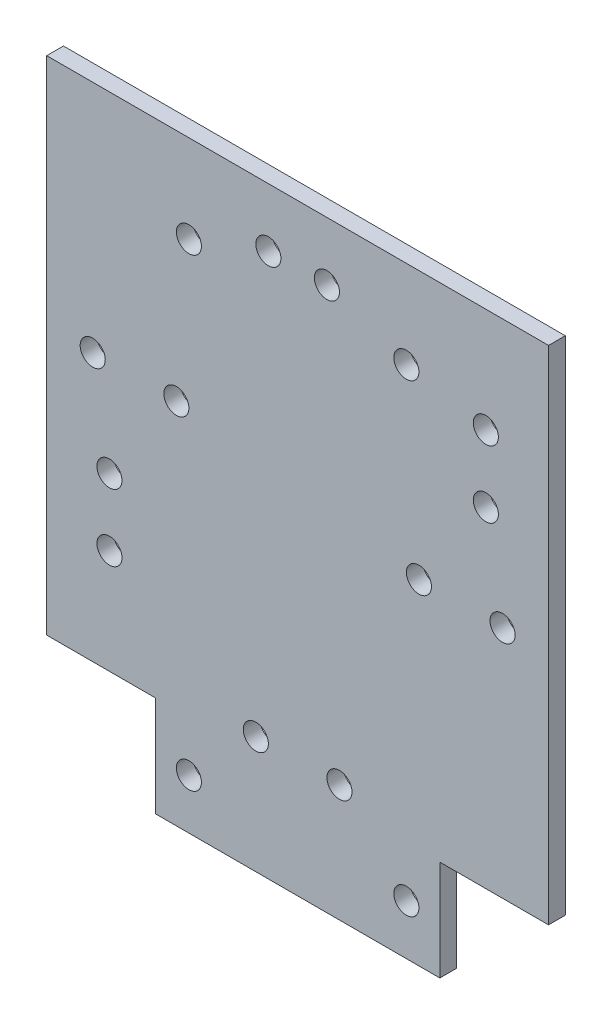
SolidWorks part; units mm, degrees
ref_plane "Plan de face" through (0, 0, 0) normal (0, 0, 1) x (1, 0, 0)
ref_plane "Plan de dessus" through (0, 0, 0) normal (0, 1, 0) x (1, 0, 0)
ref_plane "Plan de droite" through (0, 0, 0) normal (1, 0, 0) x (0, 0, -1)
sketch "Esquisse1" plane through (0, 0, 0) normal (0, 0, 1) x (1, 0, 0)
  line L0 (57.7642, 1.5445) -> (57.7642, -6.4555) construction
  line L1 (5.2642, 14.0445) -> (65.2642, 14.0445)
  line L2 (5.2642, 14.0445) -> (5.2642, -45.9555)
  line L3 (18.2642, -57.9555) -> (52.2642, -57.9555)
  line L4 (65.2642, 14.0445) -> (65.2642, -45.9555)
  line L5 (40.2642, -43.9555) -> (30.2642, -43.9555) construction
  line L6 (59.7642, -17.9555) -> (49.7642, -17.9555) construction
  line L7 (5.2642, -45.9555) -> (18.2642, -45.9555)
  line L8 (22.2642, 3.5445) -> (48.2642, 3.5445) construction
  line L9 (18.2642, -57.9555) -> (18.2642, -45.9555)
  line L10 (31.7642, 7.0445) -> (38.7642, 7.0445) construction
  line L11 (25.7642, 2.0445) -> (44.7642, 2.0445) construction
  line L12 (22.2642, -51.9555) -> (48.2642, -51.9555) construction
  line L13 (25.7642, 2.0445) -> (25.7642, -37.9555) construction
  line L14 (65.2642, -45.9555) -> (52.2642, -45.9555)
  line L15 (52.2642, -57.9555) -> (52.2642, -45.9555)
  line L16 (25.7642, -37.9555) -> (44.7642, -37.9555) construction
  line L17 (44.7642, 2.0445) -> (44.7642, -37.9555) construction
  line L18 (12.7642, -33.4555) -> (12.7642, -25.4555) construction
  line L19 (20.7642, -13.9555) -> (10.7642, -13.9555) construction
  circle A0 centre (57.7642, 1.5445) radius 1.5
  circle A1 centre (57.7642, -6.4555) radius 1.5
  circle A2 centre (12.7642, -33.4555) radius 1.5
  circle A3 centre (12.7642, -25.4555) radius 1.5
  circle A4 centre (40.2642, -43.9555) radius 1.5
  circle A5 centre (30.2642, -43.9555) radius 1.5
  circle A6 centre (49.7642, -17.9555) radius 1.5
  circle A7 centre (59.7642, -17.9555) radius 1.5
  circle A8 centre (31.7642, 7.0445) radius 1.5
  circle A9 centre (38.7642, 7.0445) radius 1.5
  circle A10 centre (22.2642, 3.5445) radius 1.5
  circle A11 centre (48.2642, 3.5445) radius 1.5
  circle A12 centre (20.7642, -13.9555) radius 1.5
  circle A13 centre (10.7642, -13.9555) radius 1.5
  circle A16 centre (22.2642, -51.9555) radius 1.5
  circle A17 centre (48.2642, -51.9555) radius 1.5
  dimension "D4" = 26
  dimension "D6" = 5
  dimension "D14" = 12.5
  dimension "D16" = 10.5
  dimension "D19" = 8
  dimension "D24" = 40
  dimension "D8" = 12
  dimension "D13" = 8
  dimension "D21" = 10
  dimension "D23" = 14
  dimension "D28" = 5
  dimension "D1" = 60
  dimension "D2" = 26
  dimension "D3" = 7
  dimension "D5" = 17
  dimension "D7" = 12
  dimension "D9" = 60
  dimension "D10" = 13
  dimension "D11" = 13
  dimension "D12" = 4
  dimension "D15" = 7.5
  dimension "D17" = 26.5
  dimension "D18" = 6
  dimension "D20" = 12.5
  dimension "D22" = 12
  dimension "D25" = 19
  dimension "D26" = 20.5
  dimension "D27" = 6
  dimension "D29" = 10
  dimension "D30" = 5
  dimension "D31" = 10
  dimension "D32" = 32
  dimension "D33" = 7.5
  dimension "D34" = 32
extrude "Extrusion1" add sketch "Esquisse1" along normal blind 2
